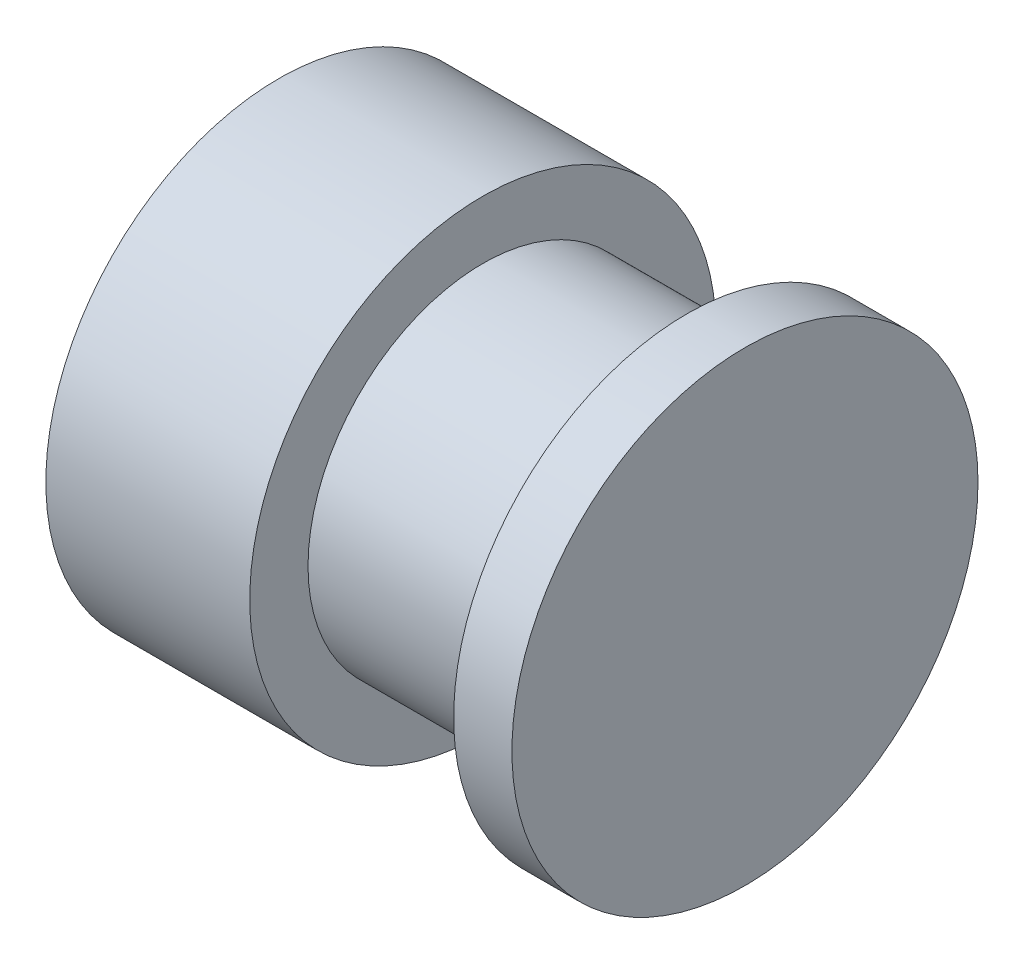
SolidWorks part; units mm, degrees
ref_plane "Front Plane" through (0, 0, 0) normal (0, 0, 1) x (1, 0, 0)
ref_plane "Top Plane" through (0, 0, 0) normal (0, 1, 0) x (1, 0, 0)
ref_plane "Right Plane" through (0, 0, 0) normal (1, 0, 0) x (0, 0, -1)
sketch "Sketch1" plane through (0, 0, 0) normal (0, 0, 1) x (1, 0, 0)
  line L0 (0, 0) -> (0, 8)
  line L1 (0, 8) -> (7, 8)
  line L2 (7, 8) -> (7, 6)
  line L3 (7, 6) -> (14, 6)
  line L4 (14, 6) -> (14, 8)
  line L5 (14, 8) -> (16, 8)
  line L6 (16, 8) -> (16, 0)
  line L7 (16, 0) -> (0, 0)
  dimension "D1" = 16
  dimension "D2" = 8
  dimension "D3" = 7
  dimension "D4" = 6
  dimension "D5" = 2
revolve "Revolve1" add sketch "Sketch1" angle 360 about L7
